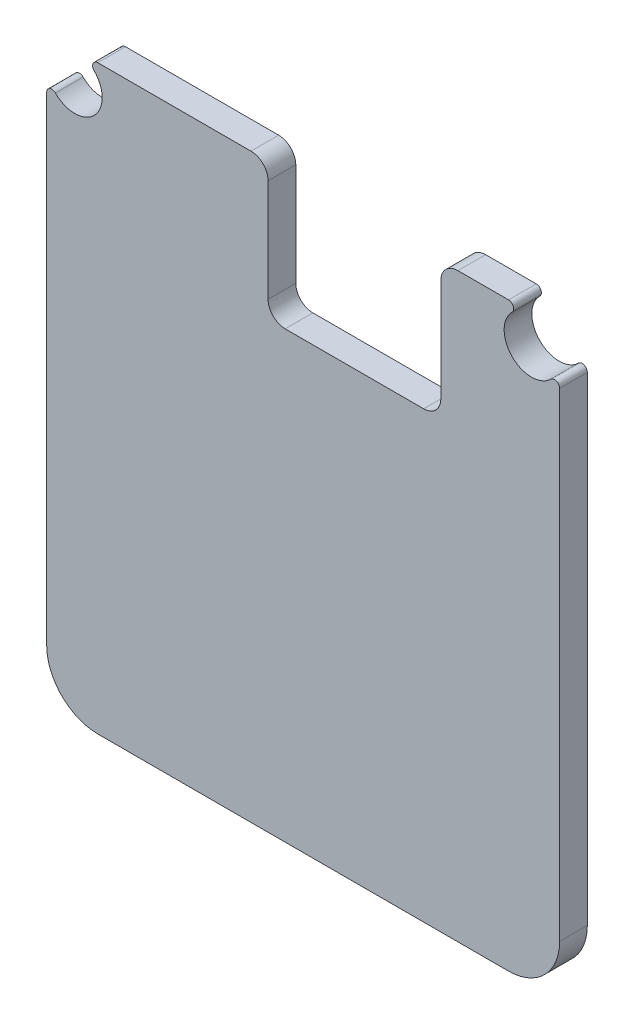
SolidWorks part; units mm, degrees
ref_plane "Front Plane" through (0, 0, 0) normal (0, 0, 1) x (1, 0, 0)
ref_plane "Top Plane" through (0, 0, 0) normal (0, 1, 0) x (1, 0, 0)
ref_plane "Right Plane" through (0, 0, 0) normal (1, 0, 0) x (0, 0, -1)
sketch "Sketch1" plane through (0, 0, 0) normal (0, 0, 1) x (1, 0, 0)
  line L0 (10, 29) -> (10, 57.013)
  line L1 (12.987, 60) -> (21.95, 60)
  line L2 (22.95, 59) -> (22.95, 53)
  line L3 (23.95, 52) -> (32.05, 52)
  line L4 (33.05, 53) -> (33.05, 59)
  line L5 (34.05, 60) -> (37.013, 60)
  line L6 (40, 57.013) -> (40, 29)
  line L7 (37, 26) -> (13, 26)
  arc A0 (13, 26) -> (10, 29) centre (13, 29) cw
  arc A1 (10, 57.013) -> (10.5121, 57.2251) centre (10.3, 57.013) cw
  arc A2 (10.5121, 57.2251) -> (12.7749, 59.4879) centre (11.6463, 58.3537) ccw
  arc A3 (12.7749, 59.4879) -> (12.987, 60) centre (12.987, 59.7) cw
  arc A4 (21.95, 60) -> (22.95, 59) centre (21.95, 59) cw
  arc A5 (22.95, 53) -> (23.95, 52) centre (23.95, 53) ccw
  arc A6 (32.05, 52) -> (33.05, 53) centre (32.05, 53) ccw
  arc A7 (33.05, 59) -> (34.05, 60) centre (34.05, 59) cw
  arc A8 (37.013, 60) -> (37.2251, 59.4879) centre (37.013, 59.7) cw
  arc A9 (37.2251, 59.4879) -> (39.4879, 57.2251) centre (38.3551, 58.3551) ccw
  arc A10 (39.4879, 57.2251) -> (40, 57.013) centre (39.7, 57.013) cw
  arc A11 (40, 29) -> (37, 26) centre (37, 29) cw
extrude "Board" add sketch "Sketch1" along normal blind 1.6194
